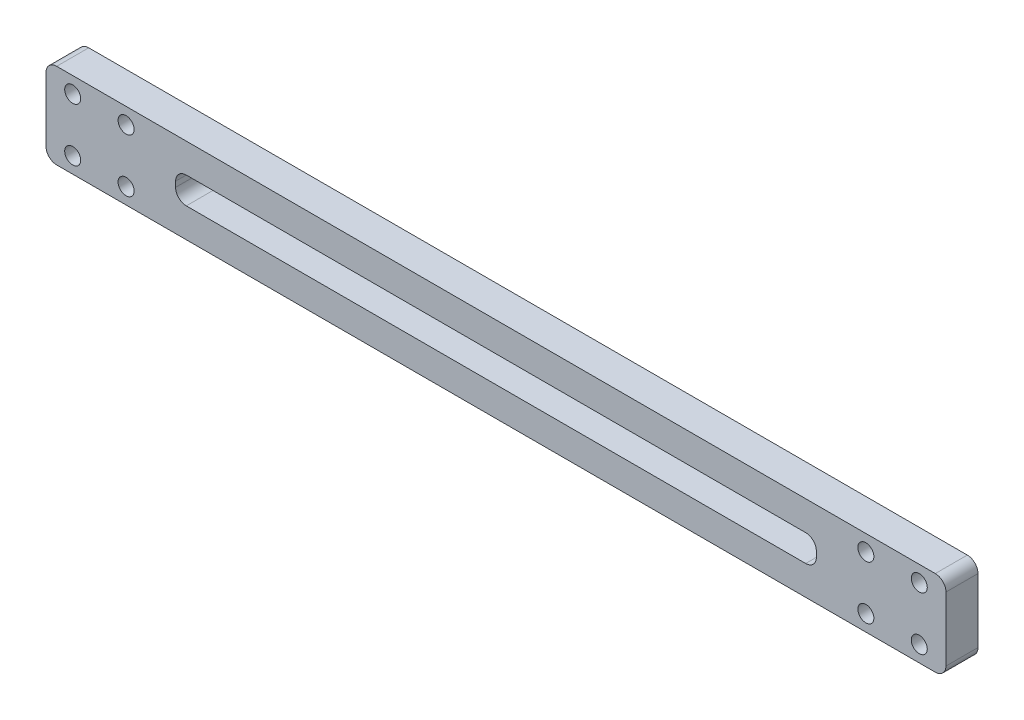
SolidWorks part; units mm, degrees
material "Thornel Mat VMA"
ref_plane "前视基准面" through (0, 0, 0) normal (0, 0, 1) x (1, 0, 0)
ref_plane "上视基准面" through (0, 0, 0) normal (0, 1, 0) x (1, 0, 0)
ref_plane "右视基准面" through (0, 0, 0) normal (1, 0, 0) x (0, 0, -1)
other "Configuration Table"
sketch "草图1" plane through (0, 0, 0) normal (0, 0, 1) x (1, 0, 0)
  line L0 (0, 0) -> (74.27, 0) construction
  line L1 (-84.27, -8) -> (84.27, -8)
  line L2 (-84.27, -8) -> (-84.27, 8)
  line L3 (-84.27, 8) -> (84.27, 8)
  line L4 (84.27, -8) -> (84.27, 8)
  line L5 (-84.27, -8) -> (84.27, 8) construction
  line L6 (-84.27, 8) -> (84.27, -8) construction
  line L7 (0, 0) -> (0, 44.8553) construction
  line L8 (69.27, -5) -> (79.27, -5) construction
  line L9 (69.27, -5) -> (69.27, 5) construction
  line L10 (69.27, 5) -> (79.27, 5) construction
  line L11 (79.27, -5) -> (79.27, 5) construction
  line L12 (69.27, -5) -> (79.27, 5) construction
  line L13 (69.27, 5) -> (79.27, -5) construction
  line L14 (-69.27, 5) -> (-79.27, -5) construction
  line L15 (-69.27, -5) -> (-79.27, 5) construction
  line L16 (-79.27, -5) -> (-79.27, 5) construction
  line L17 (-69.27, 5) -> (-79.27, 5) construction
  line L18 (-69.27, -5) -> (-69.27, 5) construction
  line L19 (-69.27, -5) -> (-79.27, -5) construction
  circle A0 centre (79.27, 5) radius 1.5
  circle A1 centre (69.27, 5) radius 1.5
  circle A2 centre (69.27, -5) radius 1.5
  circle A3 centre (79.27, -5) radius 1.5
  circle A4 centre (-79.27, -5) radius 1.5
  circle A5 centre (-69.27, -5) radius 1.5
  circle A6 centre (-69.27, 5) radius 1.5
  circle A7 centre (-79.27, 5) radius 1.5
  point P0 (0, 0)
  dimension "D3" = 3
  dimension "D1" = 69.27
  dimension "D2" = 10
  dimension "D4" = 3
  dimension "D5" = 5
extrude "凸台-拉伸1" add sketch "草图1" along normal blind 6
fillet "圆角1" radius 2 4 edges at (84.27, -8, 3) (-84.27, -8, 3) (-84.27, 8, 3) (84.27, 8, 3)
sketch "草图2" plane through (0, 0, 6) normal (0, 0, 1) x (1, 0, 0)
  line L1 (-60, -2.5) -> (60, -2.5)
  line L2 (-60, -2.5) -> (-60, 2.5)
  line L3 (-60, 2.5) -> (60, 2.5)
  line L4 (60, -2.5) -> (60, 2.5)
  line L5 (-60, -2.5) -> (60, 2.5) construction
  line L6 (-60, 2.5) -> (60, -2.5) construction
  point P0 (0, 0)
  dimension "D1" = 5
  dimension "D2" = 120
extrude "切除-拉伸1" cut sketch "草图2" against normal blind 6
fillet "圆角2" radius 2 4 edges at (60, -2.5, 3) (-60, -2.5, 3) (60, 2.5, 3) (-60, 2.5, 3)
